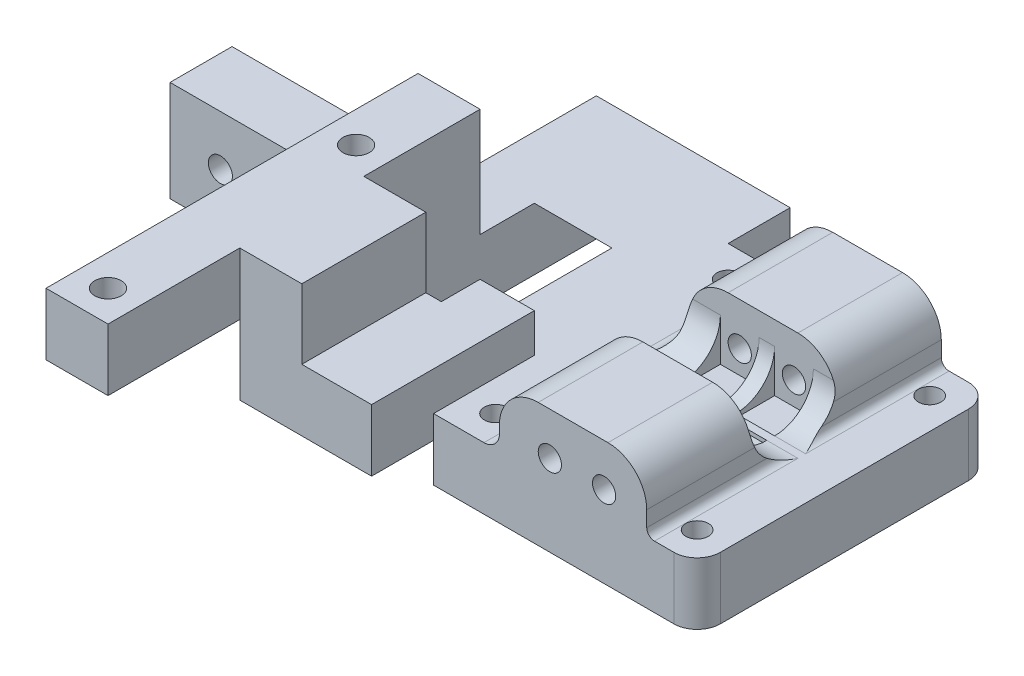
SolidWorks part; units mm, degrees
ref_plane "Front" through (0, 0, 0) normal (0, 0, 1) x (1, 0, 0)
ref_plane "Top" through (0, 0, 0) normal (0, 1, 0) x (1, 0, 0)
ref_plane "Right" through (0, 0, 0) normal (1, 0, 0) x (0, 0, -1)
sketch "Sketch1" plane through (0, 0, 0) normal (0, 1, 0) x (1, 0, 0)
  line L1 (0, 0) -> (300, 0)
  line L2 (0, 0) -> (0, -20)
  line L3 (0, -20) -> (300, -20)
  line L4 (300, 0) -> (300, -20)
  dimension "D1" = 20
  dimension "D2" = 300
extrude "Boss-Extrude1" add sketch "Sketch1" along normal blind 8
sketch "Sketch2" plane through (0, 0, 20) normal (0, 0, 1) x (1, 0, 0)
  line L0 (0, 8) -> (300, 8) construction
  line L1 (0, 0) -> (34, 0)
  line L2 (0, 0) -> (0, 8)
  line L3 (0, 8) -> (34, 8)
  line L4 (34, 0) -> (34, 8)
  line L5 (266, 8) -> (300, 8)
  line L6 (300, 0) -> (300, 8)
  line L7 (266, 0) -> (300, 0)
  line L8 (266, 0) -> (266, 8)
  dimension "D1" = 34
  dimension "D2" = 2
extrude "Boss-Extrude2" add sketch "Sketch2" along normal blind 9
sketch "Sketch3" plane through (0, 0, 0) normal (0, 0, -1) x (-1, 0, 0)
  line L0 (-300, 8) -> (0, 8) construction
  line L1 (0, 0) -> (-34, 0)
  line L2 (0, 0) -> (0, 8)
  line L3 (0, 8) -> (-34, 8)
  line L4 (-34, 0) -> (-34, 8)
  line L5 (-300, 0) -> (-300, 8)
  line L6 (-266, 8) -> (-300, 8)
  line L7 (-266, 0) -> (-266, 8)
  line L8 (-266, 0) -> (-300, 0)
  dimension "D1" = 34
  dimension "D2" = 2
extrude "Boss-Extrude3" add sketch "Sketch3" along normal blind 9
sketch "Sketch4" plane through (0, 8, 0) normal (0, 1, 0) x (1, 0, 0)
  line L0 (0, 9) -> (34, 9) construction
  line L1 (0, 9) -> (0, -29) construction
  circle A0 centre (4, 5) radius 1.45
  circle A1 centre (30, 5) radius 1.45
  circle A2 centre (30, -25) radius 1.45
  circle A3 centre (4, -25) radius 1.45
  circle A4 centre (296, -25) radius 1.45
  circle A5 centre (296, 5) radius 1.45
  circle A6 centre (270, -25) radius 1.45
  circle A7 centre (270, 5) radius 1.45
  dimension "D1" = 2.9
  dimension "D2" = 4
  dimension "D3" = 4
  dimension "D4" = 2
  dimension "D5" = 2
  dimension "D6" = 2
extrude "Cut-Extrude1" cut sketch "Sketch4" against normal through all
sketch "Sketch5" plane through (0, 0, 20) normal (0, 0, 1) x (1, 0, 0)
  line L0 (34, 8) -> (266, 8) construction
  line L1 (266, 0) -> (241, 0)
  line L2 (266, 0) -> (266, 8)
  line L3 (266, 8) -> (241, 8)
  line L4 (241, 0) -> (241, 8)
  dimension "D1" = 25
extrude "Boss-Extrude4" add sketch "Sketch5" along normal blind 17
sketch "Sketch6" plane through (0, 0, 0) normal (0, 0, -1) x (-1, 0, 0)
  line L0 (-266, 0) -> (-34, 0) construction
  line L1 (-266, 8) -> (-241, 8)
  line L2 (-266, 8) -> (-266, 0)
  line L3 (-266, 0) -> (-241, 0)
  line L4 (-241, 8) -> (-241, 0)
  dimension "D1" = 25
extrude "Boss-Extrude5" add sketch "Sketch6" along normal blind 17
sketch "Sketch12" plane through (0, 0, 37) normal (0, 0, 1) x (1, 0, 0)
  line L0 (241, 0) -> (266, 0) construction
  line L1 (241, 8) -> (249, 8)
  line L2 (241, 8) -> (241, 0)
  line L3 (241, 0) -> (249, 0)
  line L4 (249, 8) -> (249, 0)
  dimension "D1" = 8
extrude "Boss-Extrude7" add sketch "Sketch12" along normal blind 17
sketch "Sketch18" plane through (0, 0, -9) normal (0, 0, -1) x (-1, 0, 0)
  line L0 (0, 8) -> (-34, 8) construction
  line L1 (-25, 8) -> (-5, 8)
  line L2 (-25, 8) -> (-25, -5)
  line L3 (-25, -5) -> (-5, -5)
  line L4 (-5, 8) -> (-5, -5)
  line L6 (-34, 8) -> (-34, 0) construction
  dimension "D1" = 20
  dimension "D2" = 9
  dimension "D3" = 13
extrude "Boss-Extrude10" add sketch "Sketch18" along normal blind 12
sketch "Sketch19" plane through (5, 0, 0) normal (-1, 0, 0) x (0, 0, 1)
  line L0 (-21, -5) -> (-21, 8) construction
  line L2 (-21, -5) -> (-9, -5) construction
  circle A0 centre (-15, 0) radius 1.6
  dimension "D1" = 3.2
  dimension "D2" = 6
  dimension "D3" = 5
extrude "Cut-Extrude9" cut sketch "Sketch19" against normal blind 20
sketch "Sketch20" plane through (0, 0, 29) normal (0, 0, 1) x (1, 0, 0)
  line L0 (34, 8) -> (0, 8) construction
  line L1 (5, 8) -> (25, 8)
  line L2 (5, 8) -> (5, -5)
  line L3 (5, -5) -> (25, -5)
  line L4 (25, 8) -> (25, -5)
  line L6 (34, 0) -> (34, 8) construction
  dimension "D1" = 20
  dimension "D2" = 9
  dimension "D3" = 13
extrude "Boss-Extrude11" add sketch "Sketch20" along normal blind 12
sketch "Sketch21" plane through (5, 0, 0) normal (-1, 0, 0) x (0, 0, 1)
  line L0 (41, 8) -> (41, -5) construction
  line L1 (41, -5) -> (29, -5) construction
  circle A0 centre (35, 0) radius 1.6
  dimension "D1" = 3.2
  dimension "D2" = 6
  dimension "D3" = 5
extrude "Cut-Extrude10" cut sketch "Sketch21" against normal blind 20
sketch "Sketch22" plane through (0, 8, 0) normal (0, 1, 0) x (1, 0, 0)
  line L0 (241, 17) -> (241, 0) construction
  line L1 (259, 9) -> (249, 9)
  line L2 (259, 9) -> (259, -29)
  line L3 (259, -29) -> (249, -29)
  line L4 (249, 9) -> (249, -29)
  line L5 (241, 17) -> (266, 17) construction
  line L6 (266, -37) -> (249, -37) construction
  dimension "D1" = 8
  dimension "D2" = 10
  dimension "D3" = 8
  dimension "D4" = 8
extrude "Cut-Extrude11" cut sketch "Sketch22" against normal through all
sketch "Sketch23" plane through (0, 0, 0) normal (0, -1, 0) x (-1, 0, 0)
  line L0 (-259, -29) -> (-259, 9) construction
  line L1 (-259, -19) -> (-267, -19)
  line L2 (-259, -19) -> (-259, -1)
  line L3 (-259, -1) -> (-267, -1)
  line L4 (-267, -19) -> (-267, -1)
  line L5 (-249, -29) -> (-259, -29) construction
  dimension "D1" = 8
  dimension "D2" = 10
  dimension "D3" = 10
extrude "Cut-Extrude12" cut sketch "Sketch23" against normal blind 4
sketch "Sketch24" plane through (259, 0, 0) normal (-1, 0, 0) x (0, 0, 1)
  line L0 (-9, 0) -> (-9, 8)
  line L1 (-9, 8) -> (-1, 8)
  line L2 (29, 8) -> (-9, 8) construction
  line L3 (-1, 8) -> (-9, 0)
  line L4 (29, 0) -> (29, 8)
  line L5 (29, 8) -> (21, 8)
  line L6 (21, 8) -> (29, 0)
  dimension "D1" = 8
  dimension "D2" = 8
extrude "Boss-Extrude12" add sketch "Sketch24" along normal blind 10
sketch "Sketch25" plane through (267, 0, 0) normal (-1, 0, 0) x (0, 0, 1)
  line L0 (19, 0) -> (19, 4)
  line L1 (19, 4) -> (15, 4)
  line L2 (1, 4) -> (19, 4) construction
  line L3 (15, 4) -> (19, 0)
  line L4 (1, 4) -> (5, 4)
  line L5 (5, 4) -> (1, 0)
  line L6 (1, 0) -> (1, 4)
  dimension "D1" = 4
  dimension "D2" = 4
extrude "Boss-Extrude13" add sketch "Sketch25" along normal blind 8
sketch "Sketch26" plane through (0, 8, 0) normal (0, 1, 0) x (1, 0, 0)
  line L0 (249, 1) -> (249, -21) construction
  line L1 (241, -54) -> (249, -54)
  line L2 (241, -54) -> (241, -6)
  line L3 (241, -6) -> (249, -6)
  line L4 (249, -54) -> (249, -6)
  dimension "D1" = 48
extrude "Boss-Extrude14" add sketch "Sketch26" along normal blind 14
sketch "Sketch27" plane through (0, 8, 0) normal (0, 1, 0) x (1, 0, 0)
  line L0 (249, -21) -> (259, -21) construction
  line L1 (249, -37) -> (257, -37)
  line L2 (249, -37) -> (249, -21)
  line L3 (249, -21) -> (257, -21)
  line L4 (257, -37) -> (257, -21)
  dimension "D1" = 8
extrude "Boss-Extrude15" add sketch "Sketch27" along normal blind 14
sketch "Sketch28" plane through (0, 0, 0) normal (0, -1, 0) x (1, 0, 0)
  line L0 (249, -9) -> (249, 29) construction
  line L1 (241, 54) -> (249, 54)
  line L2 (241, 54) -> (241, 14)
  line L3 (241, 14) -> (249, 14)
  line L4 (249, 54) -> (249, 14)
  dimension "D1" = 40
extrude "Cut-Extrude13" cut sketch "Sketch28" against normal blind 14
sketch "Sketch30" plane through (257, 0, 0) normal (1, 0, 0) x (0, 0, -1)
  line L0 (-37, 22) -> (-21, 22) construction
  line L1 (-21, 22) -> (-37, 22)
  line L2 (-21, 22) -> (-21, 8)
  line L3 (-21, 8) -> (-37, 8)
  line L4 (-37, 22) -> (-37, 8)
extrude "Boss-Extrude16" add sketch "Sketch30" along normal blind 9
sketch "Sketch31" plane through (0, 0, 0) normal (0, -1, 0) x (-1, 0, 0)
  line L1 (-249, -37) -> (-266, -37)
  line L2 (-249, -37) -> (-249, -29)
  line L3 (-249, -29) -> (-266, -29)
  line L4 (-266, -37) -> (-266, -29)
extrude "Cut-Extrude14" cut sketch "Sketch31" against normal blind 5
sketch "Sketch32" plane through (266, 0, 0) normal (1, 0, 0) x (0, 0, -1)
  line L0 (-37, 5) -> (-37, 22) construction
  line L1 (-21, 22) -> (-37, 22)
  line L2 (-21, 22) -> (-21, 13)
  line L3 (-21, 13) -> (-37, 13)
  line L4 (-37, 22) -> (-37, 13)
  dimension "D1" = 9
extrude "Cut-Extrude15" cut sketch "Sketch32" against normal blind 9
sketch "Sketch33" plane through (249, 0, 0) normal (-1, 0, 0) x (0, 0, 1)
  line L0 (29, 5) -> (24, 5)
  line L1 (21, 8) -> (29, 0) construction
  line L2 (24, 5) -> (29, 0)
  line L3 (29, 0) -> (29, 5)
extrude "Cut-Extrude16" cut sketch "Sketch33" against normal blind 10
sketch "Sketch34" plane through (0, 0, 29) normal (0, 0, 1) x (1, 0, 0)
  line L1 (266, 5) -> (259, 5)
  line L2 (266, 5) -> (266, 0)
  line L3 (266, 0) -> (259, 0)
  line L4 (259, 5) -> (259, 0)
extrude "Cut-Extrude17" cut sketch "Sketch34" against normal blind 5
sketch "Sketch35" plane through (0, 0, 21) normal (0, 0, -1) x (-1, 0, 0)
  line L0 (-249, 8) -> (-259, 8) construction
  line L1 (-259, 8) -> (-266, 8)
  line L2 (-259, 8) -> (-259, 13)
  line L3 (-259, 13) -> (-266, 13)
  line L4 (-266, 8) -> (-266, 13)
  line L5 (-266, 8) -> (-259, 8) construction
  line L6 (-266, 8) -> (-266, 13) construction
extrude "Boss-Extrude17" add sketch "Sketch35" along normal blind 5
sketch "Sketch36" plane through (0, 22, 0) normal (0, 1, 0) x (1, 0, 0)
  line L0 (241, -54) -> (249, -54) construction
  line L1 (249, -54) -> (249, -37) construction
  circle A0 centre (245, -50) radius 1.7
  circle A1 centre (245, -18) radius 1.7
  dimension "D1" = 3.4
  dimension "D2" = 4
  dimension "D3" = 4
  dimension "D4" = 2
extrude "Cut-Extrude18" cut sketch "Sketch36" against normal through all
sketch "Sketch37" plane through (0, 8, 0) normal (0, 1, 0) x (1, 0, 0)
  line L0 (241, -6) -> (171, -6)
  line L1 (241, -6) -> (241, -14) construction
  line L2 (241, -6) -> (241, -14)
  line L3 (241, -14) -> (241, -20) construction
  line L4 (241, -14) -> (171, -14)
  line L5 (171, -14) -> (171, -6)
  dimension "D1" = 70
extrude "Boss-Extrude18" add sketch "Sketch37" along normal blind 5
sketch "Sketch39" plane through (0, 8, 0) normal (0, 1, 0) x (1, 0, 0)
  line L0 (34, -20) -> (241, -20) construction
  line L1 (241, -14) -> (175, -14)
  line L2 (241, -14) -> (241, -20)
  line L3 (241, -20) -> (175, -20)
  line L4 (175, -14) -> (175, -20)
  dimension "D1" = 66
extrude "Cut-Extrude19" cut sketch "Sketch39" against normal through all
sketch "Sketch40" plane through (0, 8, 0) normal (0, 1, 0) x (1, 0, 0)
  line L1 (5, 9) -> (25, 9)
  line L2 (5, 9) -> (5, 21)
  line L3 (5, 21) -> (25, 21)
  line L4 (25, 9) -> (25, 21)
extrude "Boss-Extrude19" add sketch "Sketch40" along normal blind 10
sketch "Sketch41" plane through (0, 18, 0) normal (0, 1, 0) x (1, 0, 0)
  line L0 (25, 21) -> (5, 21) construction
  line L1 (25, 21) -> (-3, 21)
  line L2 (25, 21) -> (25, 9)
  line L3 (25, 9) -> (-3, 9)
  line L4 (-3, 21) -> (-3, 9)
  line L5 (5, 9) -> (25, 9) construction
  line L6 (25, 9) -> (25, 21) construction
  line L7 (5, 21) -> (5, 9) construction
  dimension "D1" = 28
  dimension "D2" = 20
extrude "Boss-Extrude20" add sketch "Sketch41" along normal blind 5 and the other way blind 5
sketch "Sketch42" plane through (-3, 0, 0) normal (-1, 0, 0) x (0, 0, 1)
  line L0 (-21, 23) -> (-9, 23) construction
  line L1 (-9, 13) -> (-9, 23) construction
  circle A0 centre (-14, 18) radius 1.5
  dimension "D1" = 3
  dimension "D2" = 5
  dimension "D3" = 5
extrude "Cut-Extrude20" cut sketch "Sketch42" against normal blind 15
sketch "Sketch43" plane through (0, 8, 0) normal (0, 1, 0) x (1, 0, 0)
  line L1 (5, -41) -> (25, -41)
  line L2 (5, -41) -> (5, -29)
  line L3 (5, -29) -> (25, -29)
  line L4 (25, -41) -> (25, -29)
extrude "Boss-Extrude21" add sketch "Sketch43" along normal blind 10
sketch "Sketch44" plane through (0, 18, 0) normal (0, 1, 0) x (1, 0, 0)
  line L0 (25, -29) -> (5, -29) construction
  line L1 (-3, -29) -> (25, -29)
  line L2 (-3, -29) -> (-3, -41)
  line L3 (-3, -41) -> (25, -41)
  line L4 (25, -29) -> (25, -41)
  line L5 (5, -41) -> (25, -41) construction
  line L6 (25, -41) -> (25, -29) construction
  line L7 (5, -29) -> (5, -41) construction
  dimension "D1" = 28
  dimension "D2" = 20
extrude "Boss-Extrude22" add sketch "Sketch44" along normal blind 5 and the other way blind 5
sketch "Sketch45" plane through (-3, 0, 0) normal (-1, 0, 0) x (0, 0, 1)
  line L0 (29, 23) -> (41, 23) construction
  line L1 (41, 13) -> (41, 23) construction
  circle A0 centre (36, 18) radius 1.5
  dimension "D1" = 3
  dimension "D2" = 5
  dimension "D3" = 5
extrude "Cut-Extrude21" cut sketch "Sketch45" against normal blind 15
sketch "Sketch49" plane through (0, 8, 0) normal (0, 1, 0) x (1, 0, 0)
  line L0 (241, 0) -> (34, 0) construction
  line L1 (34, -20) -> (175, -20) construction
  line L2 (0, 9) -> (0, -29) construction
  circle A0 centre (78, -8) radius 1.45
  circle A1 centre (78, -12) radius 1.45
  dimension "D1" = 2.9
  dimension "D2" = 2.9
  dimension "D3" = 8
  dimension "D4" = 8
  dimension "D5" = 78
  dimension "D6" = 78
extrude "Cut-Extrude23" cut sketch "Sketch49" against normal through all
sketch "Sketch50" plane through (-3, 0, 0) normal (-1, 0, 0) x (0, 0, 1)
  line L1 (63.9113, -17.5223) -> (-35.1617, -17.5223)
  line L2 (63.9113, -17.5223) -> (63.9113, 34.5971)
  line L3 (63.9113, 34.5971) -> (-35.1617, 34.5971)
  line L4 (-35.1617, -17.5223) -> (-35.1617, 34.5971)
extrude "Cut-Extrude24" cut sketch "Sketch50" against normal blind 220
sketch "Sketch51" plane through (0, 8, 0) normal (0, 1, 0) x (1, 0, 0)
  line L0 (241, 0) -> (217, 0) construction
  line L1 (217, -6) -> (238, -6)
  line L2 (217, -6) -> (217, 0)
  line L3 (217, 0) -> (238, 0)
  line L4 (238, -6) -> (238, 0)
  dimension "D1" = 21
extrude "Cut-Extrude25" cut sketch "Sketch51" against normal through all
sketch "Sketch52" plane through (0, 0, 6) normal (0, 0, -1) x (-1, 0, 0)
  line L0 (-217, 13) -> (-217, 0) construction
  circle A0 centre (-223.5, 6.5) radius 1.55
  circle A1 centre (-231.5, 6.5) radius 1.55
  dimension "D1" = 3.1
  dimension "D2" = 3.1
  dimension "D3" = 6.5
  dimension "D4" = 8
extrude "Cut-Extrude26" cut sketch "Sketch52" against normal through all
fillet "Fillet5" radius 3 2 edges at (300, 4, -9) (300, 4, 29)
sketch "Sketch54" plane through (0, 8, 0) normal (0, 1, 0) x (1, 0, 0)
  line L0 (266, 9) -> (297, 9) construction
  line L1 (293.5, 9) -> (274.5, 9)
  line L2 (293.5, 9) -> (293.5, -4.5)
  line L3 (293.5, -4.5) -> (274.5, -4.5)
  line L4 (274.5, 9) -> (274.5, -4.5)
  line L5 (297, -29) -> (266, -29) construction
  line L6 (293.5, -29) -> (274.5, -29)
  line L7 (293.5, -29) -> (293.5, -15.5)
  line L8 (293.5, -15.5) -> (274.5, -15.5)
  line L9 (274.5, -29) -> (274.5, -15.5)
  line L10 (300, -26) -> (300, 6) construction
  dimension "D1" = 13.5
  dimension "D2" = 13.5
  dimension "D3" = 19
  dimension "D4" = 19
  dimension "D5" = 6.5
  dimension "D6" = 6.5
extrude "Boss-Extrude26" add sketch "Sketch54" along normal blind 8
fillet "Fillet6" radius 5 2 edges at (284, 8, 4.5) (284, 8, 15.5)
sketch "Sketch55" plane through (0, 0, -9) normal (0, 0, -1) x (-1, 0, 0)
  line L0 (-293.5, 16) -> (-274.5, 16) construction
  line L1 (-293.5, 16) -> (-293.5, 8) construction
  line L2 (-274.5, 16) -> (-274.5, 8) construction
  circle A0 centre (-288, 10.5) radius 1.5
  circle A1 centre (-281, 10.5) radius 1.5
  dimension "D1" = 3
  dimension "D2" = 3
  dimension "D3" = 5.5
  dimension "D4" = 5.5
  dimension "D5" = 5.5
  dimension "D6" = 6.5
extrude "Cut-Extrude27" cut sketch "Sketch55" against normal through all
fillet "Fillet7" radius 5 4 edges at (274.5, 16, -2.25) (293.5, 16, -2.25) (274.5, 16, 22.25) (293.5, 16, 22.25)
fillet "Fillet8" radius 1 2 edges at (293.5, 8, 0.25) (293.5, 8, 19.75)
fillet "Fillet9" radius 2 2 edges at (274.5, 8, 0.25) (274.5, 8, 19.75)
sketch "Sketch56" plane through (0, 16, 0) normal (0, 1, 0) x (1, 0, 0)
  line L0 (288.5, -15.5) -> (279.5, -15.5) construction
  line L1 (288.5, -29) -> (288.5, -15.5) construction
  line L2 (283.5, -15.5) -> (278.5, -15.5)
  line L3 (283.5, -15.5) -> (283.5, -10.5)
  line L4 (283.5, -10.5) -> (278.5, -10.5)
  line L5 (285.5, -15.5) -> (290.5, -15.5)
  line L6 (285.5, -15.5) -> (285.5, -10.5)
  line L7 (285.5, -10.5) -> (290.5, -10.5)
  line L8 (290.5, -15.5) -> (290.5, -10.5)
  line L9 (279.5, -4.5) -> (288.5, -4.5) construction
  line L10 (283.5, -4.5) -> (278.5, -4.5)
  line L11 (283.5, -4.5) -> (283.5, -9.5)
  line L12 (283.5, -9.5) -> (278.5, -9.5)
  line L13 (278.5, -4.5) -> (278.5, -9.5)
  line L14 (278.5, -15.5) -> (278.5, -10.5)
  line L15 (285.5, -4.5) -> (290.5, -4.5)
  line L16 (285.5, -4.5) -> (285.5, -9.5)
  line L17 (285.5, -9.5) -> (290.5, -9.5)
  line L18 (290.5, -4.5) -> (290.5, -9.5)
  line L19 (279.5, -15.5) -> (279.5, -29) construction
  line L20 (288.5, -4.5) -> (288.5, 9) construction
  line L21 (279.5, 9) -> (279.5, -4.5) construction
  dimension "D1" = 5
  dimension "D2" = 5
  dimension "D3" = 5
  dimension "D4" = 5
  dimension "D5" = 5
  dimension "D6" = 5
  dimension "D7" = 5
  dimension "D8" = 5
  dimension "D9" = 3
  dimension "D10" = 4
  dimension "D11" = 3
  dimension "D12" = 4
extrude "Cut-Extrude28" cut sketch "Sketch56" against normal blind 8.5
